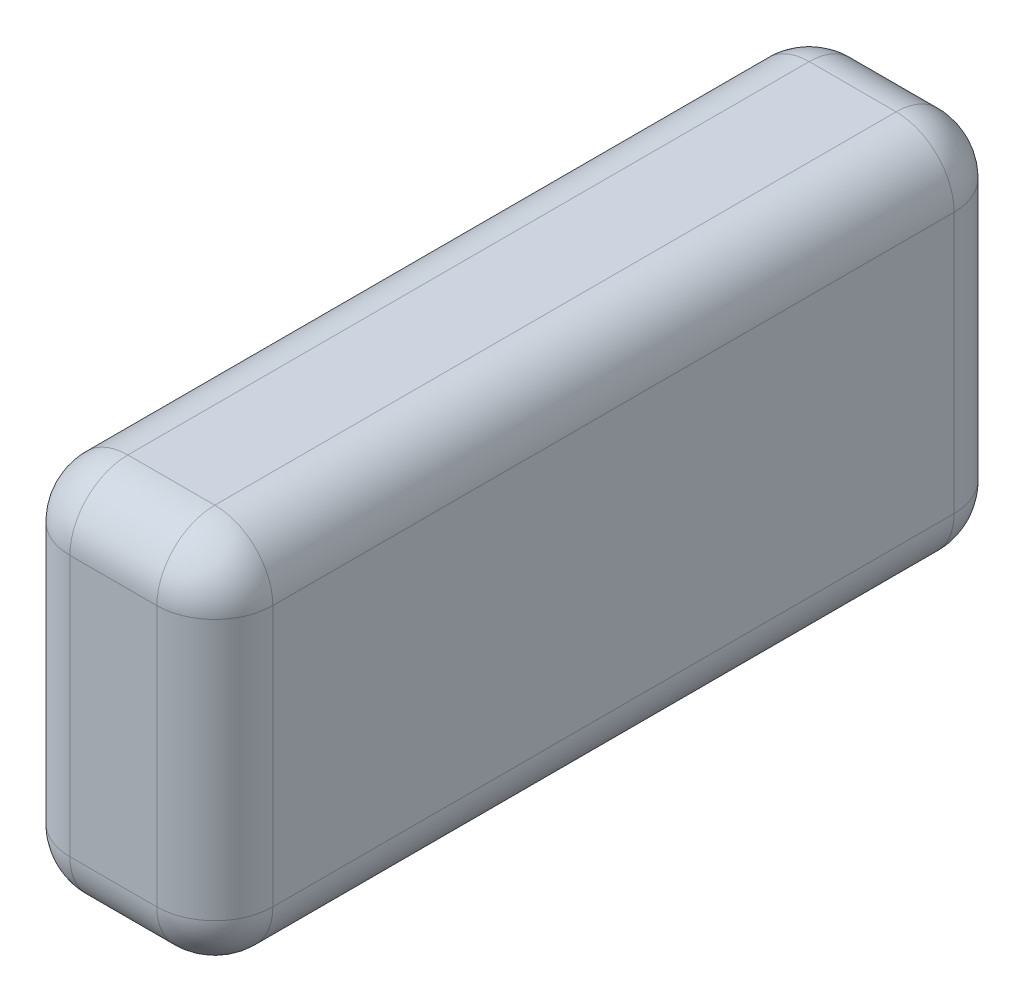
SolidWorks part; units mm, degrees
ref_plane "正面" through (0, 0, 0) normal (0, 0, 1) x (1, 0, 0)
ref_plane "平面" through (0, 0, 0) normal (0, 1, 0) x (1, 0, 0)
ref_plane "右側面" through (0, 0, 0) normal (1, 0, 0) x (0, 0, -1)
sketch "ｽｹｯﾁ1" plane through (0, 0, 0) normal (0, 0, 1) x (1, 0, 0)
  line L1 (14, -26) -> (-14, -26)
  line L2 (14, -26) -> (14, 26)
  line L3 (14, 26) -> (-14, 26)
  line L4 (-14, -26) -> (-14, 26)
  line L5 (14, -26) -> (-14, 26) construction
  line L6 (14, 26) -> (-14, -26) construction
  point P0 (0, 0)
  dimension "D1" = 52
  dimension "D2" = 28
extrude "ﾎﾞｽ - 押し出し1" add sketch "ｽｹｯﾁ1" along normal blind 110
fillet "ﾌｨﾚｯﾄ1" radius 8 12 edges at (14, 0, 0) (14, 0, 110) (-14, 0, 110) (-14, 0, 0) (-14, 26, 55) (14, 26, 55) (-14, -26, 55) (14, -26, 55) (0, -26, 0) (0, 26, 0) (0, 26, 110) (0, -26, 110)
